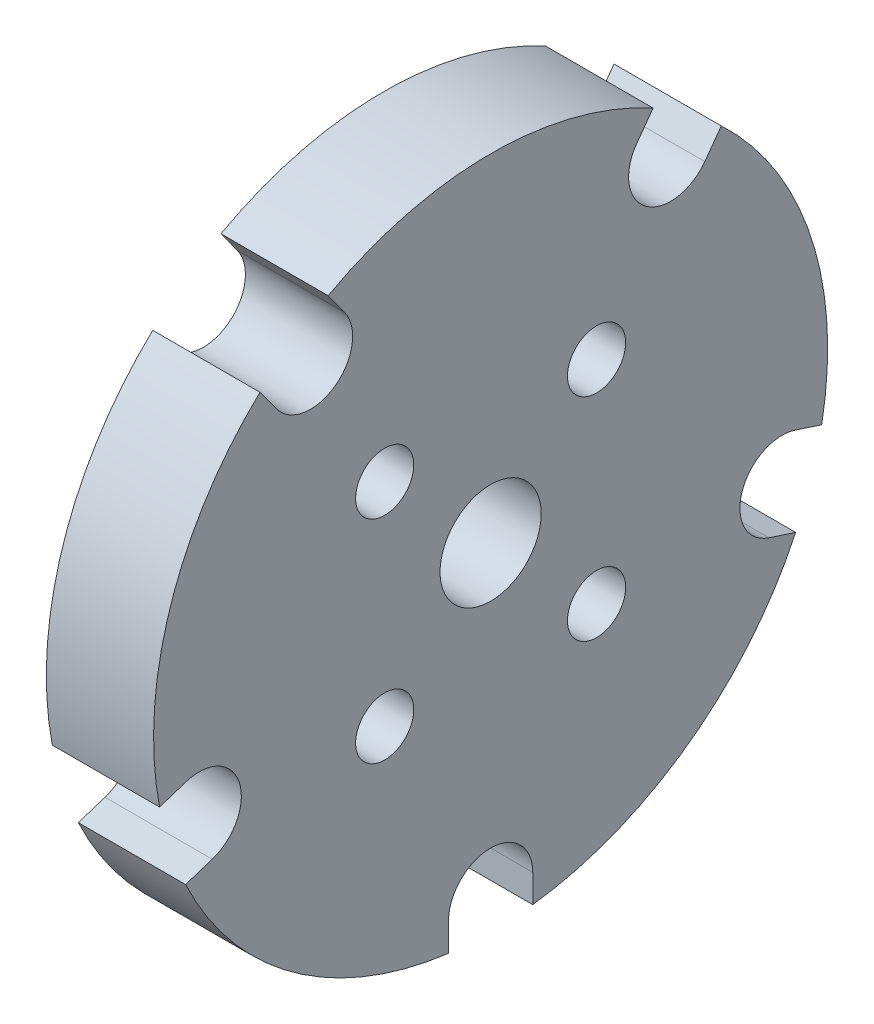
SolidWorks part; units mm, degrees
ref_plane "Plan de face" through (0, 0, 0) normal (0, 0, 1) x (1, 0, 0)
ref_plane "Plan de dessus" through (0, 0, 0) normal (0, 1, 0) x (1, 0, 0)
ref_plane "Plan de droite" through (0, 0, 0) normal (1, 0, 0) x (0, 0, -1)
sketch "Esquisse1" plane through (0, 0, 0) normal (1, 0, 0) x (0, 0, -1)
  circle A0 centre (0, 0) radius 22
  dimension "D1" = 44
extrude "Boss.-Extru.1" add sketch "Esquisse1" along normal blind 7
sketch "Esquisse5" plane through (7, 0, 0) normal (1, 0, 0) x (0, 0, -1)
  line L0 (0, -20) -> (0, -24) construction
  line L1 (2.75, -20) -> (2.75, -24)
  line L2 (-2.75, -20) -> (-2.75, -24)
  line L3 (0, 0) -> (0, -20) construction
  arc A0 (2.75, -20) -> (-2.75, -20) centre (0, -20) ccw
  arc A1 (-2.75, -24) -> (2.75, -24) centre (0, -24) ccw
  circle A2 centre (0, 0) radius 22 construction
  point P3 (0, -22)
  dimension "D2" = 5.5
  dimension "D1" = 20
extrude "Enlèv. mat.-Extru.1" cut sketch "Esquisse5" against normal up to next
pattern_circular "Répétition circulaire1" count 5 over 360 about axis through (0, 0, 0) along (1, 0, 0) of "Enlèv. mat.-Extru.1"
sketch "Esquisse6" plane through (7, 0, 0) normal (1, 0, 0) x (0, 0, -1)
  circle A0 centre (0, 0) radius 3.3
  dimension "D1" = 6.6
extrude "Enlèv. mat.-Extru.2" cut sketch "Esquisse6" against normal up to next
hole_wizard "Chambrage pour vis à tête ronde bombée #61" positions "Esquisse7" profile "Esquisse8" counterbore size "#6" standard "Ansi Inch" end condition through all
sketch "Esquisse7" plane through (0, 0, 0) normal (-1, 0, 0) x (0, 0, 1)
  line L0 (-6.9148, 6.9148) -> (-6.9148, -6.9148) construction
  line L1 (-6.9148, -6.9148) -> (6.9148, -6.9148) construction
  line L2 (6.9148, -6.9148) -> (6.9148, 6.9148) construction
  line L3 (6.9148, 6.9148) -> (-6.9148, 6.9148) construction
  line L5 (0, 6.9148) -> (0, 0) construction
  line L6 (0, 0) -> (-6.9148, 0) construction
  point P0 (-6.9148, 6.9148)
  point P2 (6.9148, 6.9148)
  point P4 (6.9148, -6.9148)
  point P6 (-6.9148, -6.9148)
  dimension "D1" = 19.558
sketch "Esquisse8" plane through (0, 6.9148, -6.9148) normal (0, 1, 0) x (0, 0, 1)
  line L0 (0, 0) -> (0, 7)
  line L1 (0, 7) -> (1.8986, 7)
  line L3 (1.8986, 7) -> (1.8986, 2.4638)
  line L4 (1.8986, 2.4638) -> (3.7706, 2.4638)
  line L5 (3.7706, 2.4638) -> (3.7706, 0)
  line L7 (3.7706, 0) -> (0, 0)
  line L11 (0, -6.35) -> (0, 107.95) construction
  dimension "Diamètre du perçage jusqu'au prochain" = 3.7973
  dimension "Profondeur du perçage jusqu'au prochain" = 7
  dimension "Diamètre du chambrage" = 7.5413
  dimension "Profondeur du chambrage" = 2.4638
